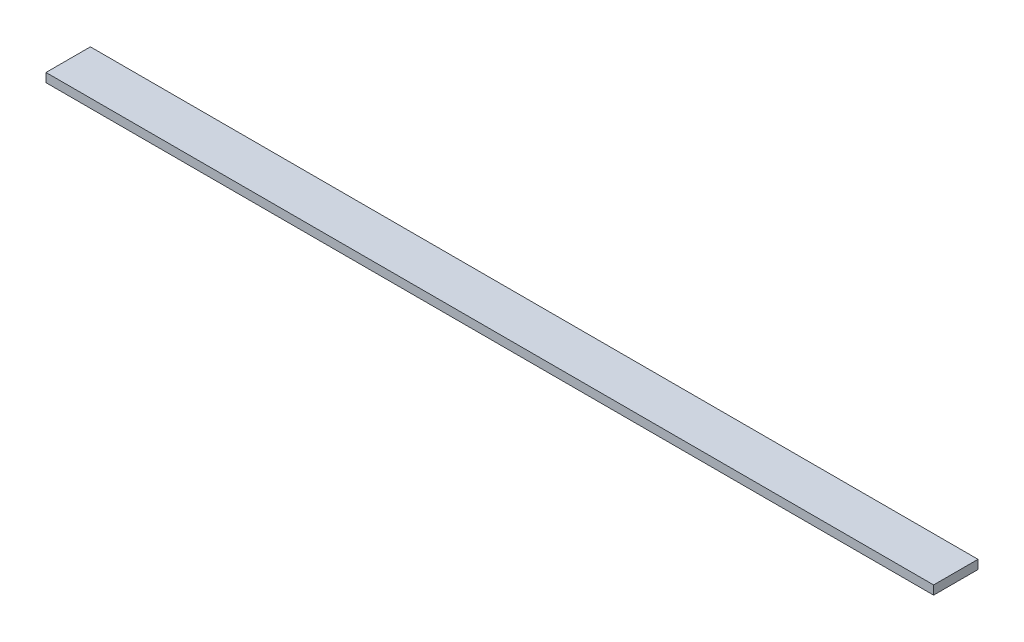
SolidWorks part; units mm, degrees
ref_plane "Front Plane" through (0, 0, 0) normal (0, 0, 1) x (1, 0, 0)
ref_plane "Top Plane" through (0, 0, 0) normal (0, 1, 0) x (1, 0, 0)
ref_plane "Right Plane" through (0, 0, 0) normal (1, 0, 0) x (0, 0, -1)
other "Configuration Table"
sketch "Sketch1" plane through (0, 0, 0) normal (0, 0, 1) x (1, 0, 0)
  line L1 (150, 1040) -> (550, 1040)
  line L2 (150, 1040) -> (150, 1044)
  line L3 (150, 1044) -> (550, 1044)
  line L4 (550, 1040) -> (550, 1044)
extrude "PACK_sarjor_alt_tutucu_ray_2_1" add sketch "Sketch1" against normal blind 20 from offset 20 separate body
